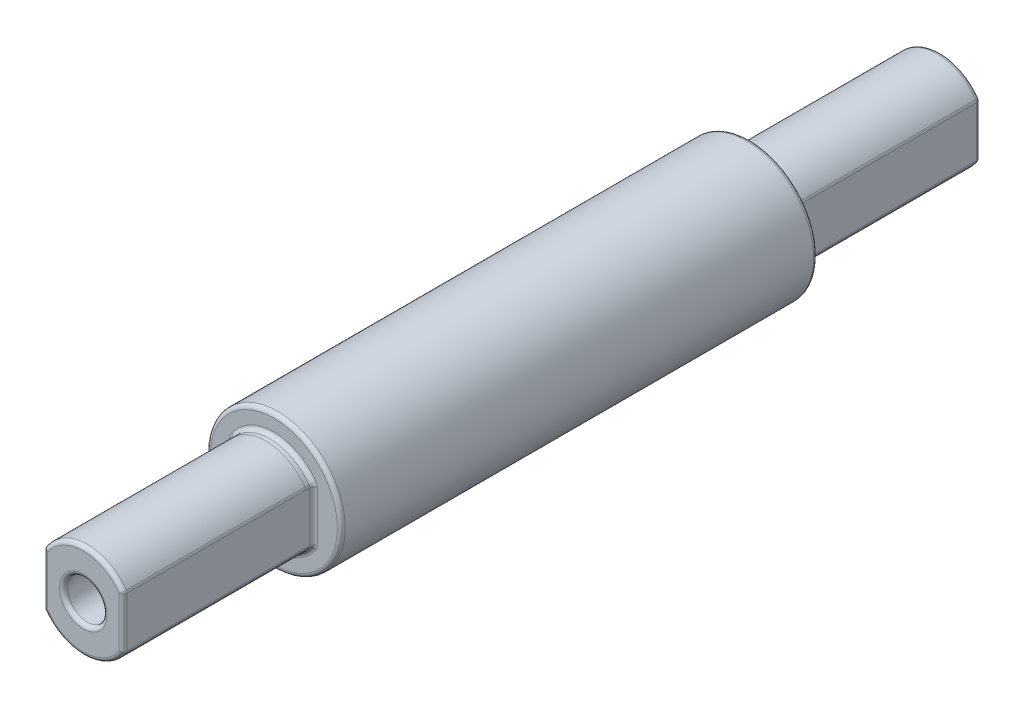
SolidWorks part; units mm, degrees
ref_plane "Alzado" through (0, 0, 0) normal (0, 0, 1) x (1, 0, 0)
ref_plane "Planta" through (0, 0, 0) normal (0, 1, 0) x (1, 0, 0)
ref_plane "Vista lateral" through (0, 0, 0) normal (1, 0, 0) x (0, 0, -1)
sketch "Croquis1" plane through (0, 0, 0) normal (1, 0, 0) x (0, 0, -1)
  line L0 (-55.0748, 0) -> (55.0748, 0) construction
  line L5 (-30, 8.5) -> (-30, 6)
  line L7 (-54, 6) -> (-54, 2.5)
  line L8 (-54, 2.5) -> (-30, 2.5)
  line L9 (0, 0) -> (0, 23.4689) construction
  line L12 (-30, 2.5) -> (0, 2.5)
  line L14 (-30, 8.5) -> (0, 8.5)
  line L16 (-30, 6) -> (-31, 6)
  line L17 (-31, 6) -> (-54, 6)
  line L18 (0, 8.5) -> (0, 2.5)
  dimension "D1" = 1
  dimension "D2" = 108
  dimension "D3" = 5
  dimension "D4" = 17
  dimension "D5" = 12
  dimension "D6" = 60
revolve "Revolución4" add sketch "Croquis1" angle 360 about L0
sketch "Croquis2" plane through (0, 0, 0) normal (1, 0, 0) x (0, 0, -1)
  line L0 (-31, -6) -> (-31, 6)
  line L2 (-54, -6) -> (-30, -6) construction
  point P3 (-31, 0)
split line "Línea de partición1"
sketch "Croquis3" plane through (0, 0, 54) normal (0, 0, 1) x (1, 0, 0)
  line L1 (-5, 3.3166) -> (5, 3.3166) construction
  line L2 (-5, 3.3166) -> (-5, -3.3166)
  line L3 (-5, -3.3166) -> (5, -3.3166) construction
  line L4 (5, 3.3166) -> (5, -3.3166)
  line L5 (-5, 3.3166) -> (5, -3.3166) construction
  line L6 (-5, -3.3166) -> (5, 3.3166) construction
  circle A0 centre (0, 0) radius 6 construction
  circle A1 centre (0, 0) radius 6 construction
  arc A2 (-5, 3.3166) -> (-5, -3.3166) centre (0, 0) ccw
  arc A3 (5, -3.3166) -> (5, 3.3166) centre (0, 0) ccw
  point P0 (0, 0)
  dimension "D1" = 10
extrude "Cortar-Extruir1" cut sketch "Croquis3" against normal up to surface (24 mm away) up to face at (6, 0, 30)
fillet "Redondeo2" radius 0.5 16 edges at (-5, 0, 30) (0, 6, 30) (0, -6, 54) (0, -6, 30) (0, 6, 54) (-5, 3.3166, 42.5) (-5, 3.3166, 30.5) (5, 3.3166, 30.5) (5, 3.3166, 42.5) (5, -3.3166, 42.5) (5, -3.3166, 30.5) (5, 0, 54) (-5, 0, 54) (5, 0, 30) (8.5, 0, 30) (2.5, 0, 54)
mirror "Simetría1" about plane through (0, 0, 0) normal (0, 0, 1) of bodies 106
